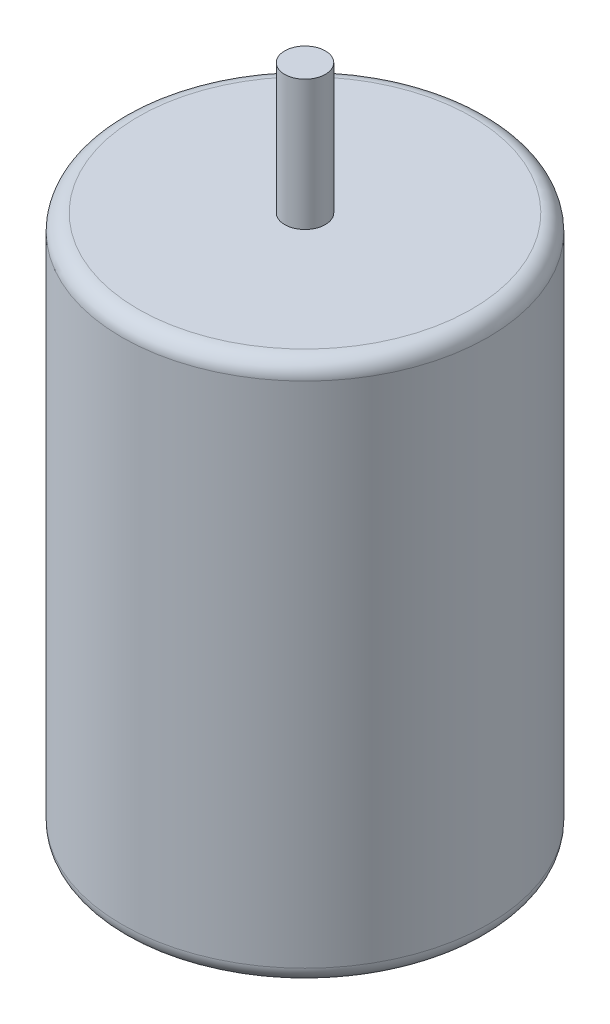
SolidWorks part; units mm, degrees
ref_plane "前基準面" through (0, 0, 0) normal (0, 0, 1) x (1, 0, 0)
ref_plane "上基準面" through (0, 0, 0) normal (0, 1, 0) x (1, 0, 0)
ref_plane "右基準面" through (0, 0, 0) normal (1, 0, 0) x (0, 0, -1)
sketch "草圖1" plane through (0, 0, 0) normal (0, 1, 0) x (1, 0, 0)
  circle A0 centre (0, 0) radius 22.5
  dimension "D1" = 45
extrude "填料-伸長1" add sketch "草圖1" along normal blind 66.5
sketch "草圖2" plane through (0, 66.5, 0) normal (0, 1, 0) x (1, 0, 0)
  circle A0 centre (0, 0) radius 2.5
  dimension "D1" = 5
extrude "填料-伸長2" add sketch "草圖2" along normal blind 16
fillet "圓角1" radius 2 2 edges at (0, 0, 22.5) (0, 66.5, 22.5)
